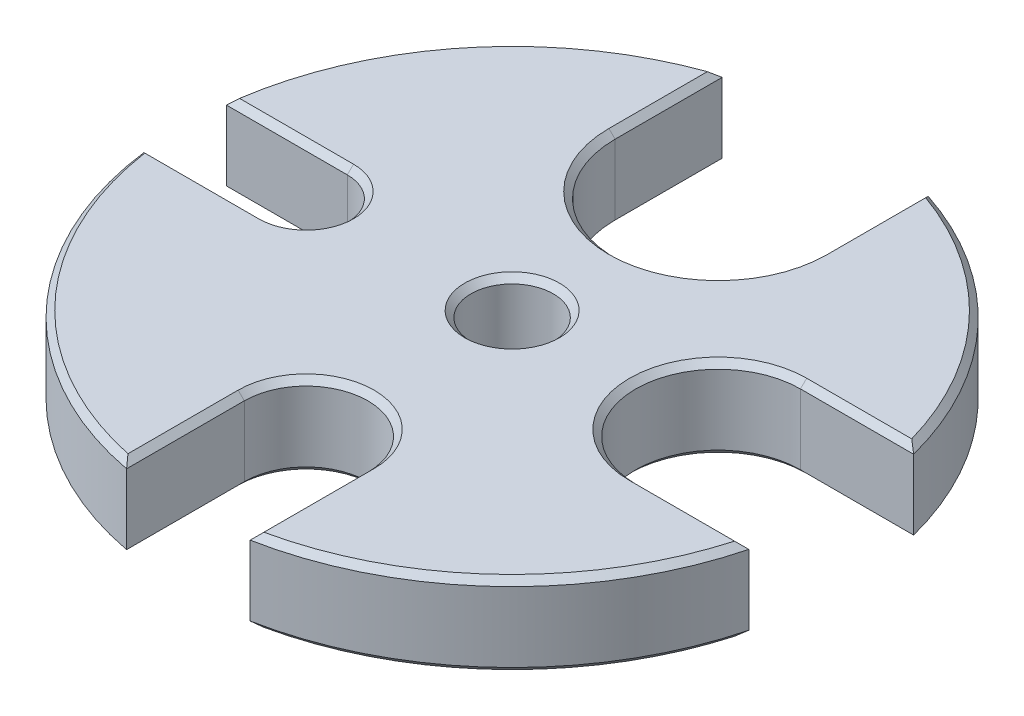
SolidWorks part; units mm, degrees
ref_plane "Front Plane" through (0, 0, 0) normal (0, 0, 1) x (1, 0, 0)
ref_plane "Top Plane" through (0, 0, 0) normal (0, 1, 0) x (1, 0, 0)
ref_plane "Right Plane" through (0, 0, 0) normal (1, 0, 0) x (0, 0, -1)
sketch "Sketch2" plane through (0, 0, 0) normal (0, 1, 0) x (1, 0, 0)
  line L0 (0, 101.6) -> (0, -101.6) construction
  line L1 (-101.6, 0) -> (101.6, 0) construction
  line L2 (63.5, 25.4) -> (98.3738, 25.4)
  line L3 (63.5, -25.4) -> (98.3738, -25.4)
  line L4 (-63.5, 12.7) -> (-100.8031, 12.7)
  line L5 (-63.5, -12.7) -> (-100.8031, -12.7)
  line L6 (-31.75, 63.5) -> (-31.75, 96.5116)
  line L7 (31.75, 63.5) -> (31.75, 96.5116)
  line L8 (19.05, -63.5) -> (19.05, -99.7981)
  line L9 (-19.05, -63.5) -> (-19.05, -99.7981)
  arc A0 (19.05, -99.7981) -> (98.3738, -25.4) centre (0, 0) ccw
  circle A1 centre (0, 0) radius 63.5 construction
  arc A2 (-31.75, 63.5) -> (31.75, 63.5) centre (0, 63.5) ccw
  arc A3 (63.5, 25.4) -> (63.5, -25.4) centre (63.5, 0) ccw
  arc A4 (19.05, -63.5) -> (-19.05, -63.5) centre (0, -63.5) ccw
  arc A5 (-63.5, -12.7) -> (-63.5, 12.7) centre (-63.5, 0) ccw
  circle A6 centre (0, 0) radius 12.7
  arc A7 (98.3738, 25.4) -> (31.75, 96.5116) centre (0, 0) ccw
  arc A8 (-100.8031, -12.7) -> (-19.05, -99.7981) centre (0, 0) ccw
  arc A9 (-31.75, 96.5116) -> (-100.8031, 12.7) centre (0, 0) ccw
  dimension "D1" = 203.2
  dimension "D2" = 127
  dimension "D3" = 63.5
  dimension "D4" = 50.8
  dimension "D5" = 38.1
  dimension "D6" = 25.4
  dimension "D7" = 25.4
extrude "Boss-Extrude1" add sketch "Sketch2" along normal blind 25.4
chamfer "Chamfer1" distance 1.905 angle 45 34 edges at (0, 0, 12.7) (80.9369, 0, -25.4) (74.1435, 0, -69.4643) (31.75, 0, -80.0058) (0, 0, -31.75) (-31.75, 0, -80.0058) (-78.4135, 0, -64.6056) (-82.1516, 0, -12.7) (-50.8, 0, 0) (-82.1516, 0, 12.7) (-74.0791, 0, 69.5331) (-19.05, 0, 81.649) (0, 0, 44.45) (19.05, 0, 81.649) (69.5043, 0, 74.106) (80.9369, 0, 25.4) (38.1, 0, 0) (0, 25.4, 12.7) (80.9369, 25.4, 25.4) (69.5043, 25.4, 74.106) (19.05, 25.4, 81.649) (0, 25.4, 44.45) (-19.05, 25.4, 81.649) (-74.0791, 25.4, 69.5331) (-82.1516, 25.4, 12.7) (-50.8, 25.4, 0) (-82.1516, 25.4, -12.7) (-78.4135, 25.4, -64.6056) (-31.75, 25.4, -80.0058) (0, 25.4, -31.75) (31.75, 25.4, -80.0058) (74.1435, 25.4, -69.4643) (80.9369, 25.4, -25.4) (38.1, 25.4, 0)
